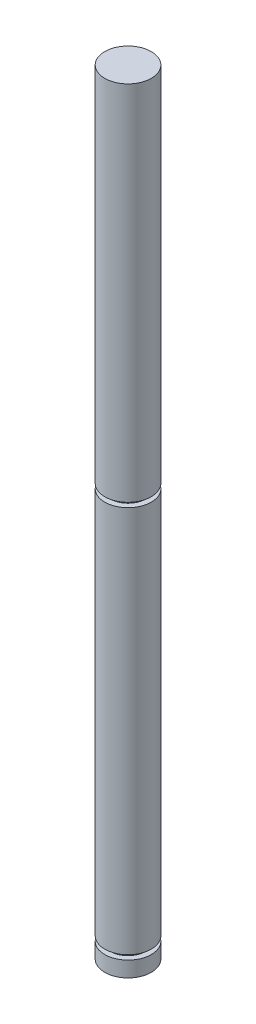
SolidWorks part; units mm, degrees
ref_plane "Front Plane" through (0, 0, 0) normal (0, 0, 1) x (1, 0, 0)
ref_plane "Top Plane" through (0, 0, 0) normal (0, 1, 0) x (1, 0, 0)
ref_plane "Right Plane" through (0, 0, 0) normal (1, 0, 0) x (0, 0, -1)
sketch "Sketch1" plane through (0, 0, 0) normal (0, 0, 1) x (1, 0, 0)
  line L0 (0, 0) -> (0, 250)
  line L1 (0, 0) -> (7.5, 0)
  line L2 (7.5, 0) -> (7.5, 5)
  line L3 (7.5, 5) -> (5.75, 5)
  line L4 (5.75, 5) -> (5.75, 6.5)
  line L5 (5.75, 6.5) -> (7.5, 6.5)
  line L6 (7.5, 6.5) -> (7.5, 131.5)
  line L7 (7.5, 131.5) -> (5.75, 131.5)
  line L8 (5.75, 131.5) -> (5.75, 133)
  line L9 (5.75, 133) -> (7.5, 133)
  line L10 (7.5, 133) -> (7.5, 250)
  line L11 (7.5, 250) -> (0, 250)
  dimension "D1" = 250
  dimension "D2" = 7.5
  dimension "D3" = 126.5
  dimension "D4" = 1.5
  dimension "D5" = 5.75
  dimension "D6" = 5
revolve "Revolve2" add sketch "Sketch1" angle 360 about L0
